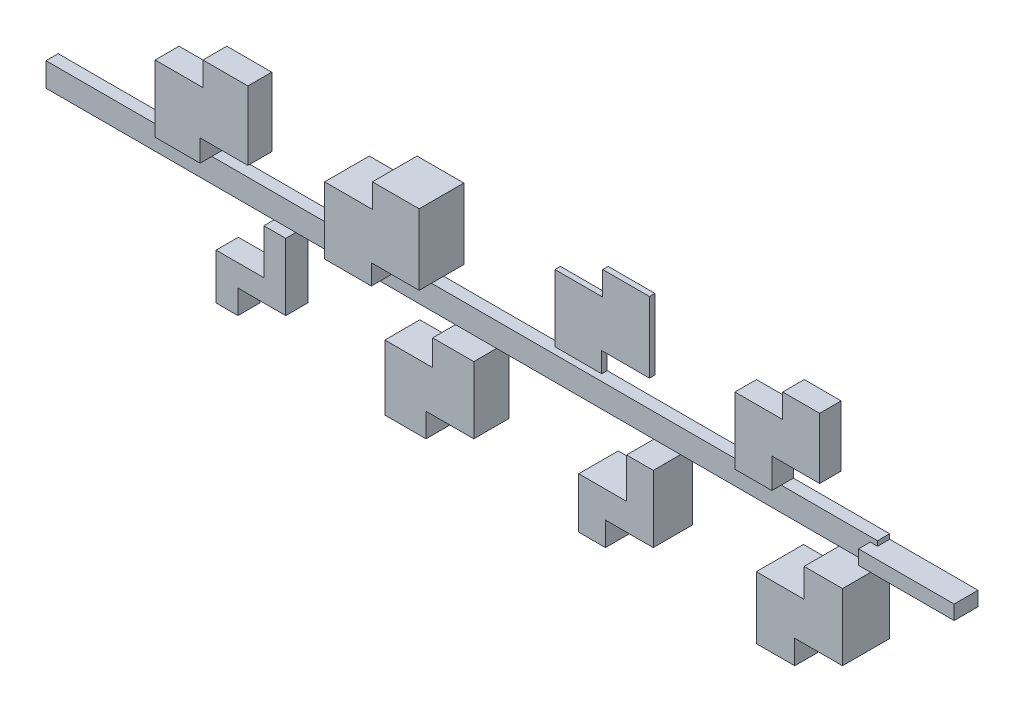
SolidWorks part; units mm, degrees
ref_plane "前视基准面" through (0, 0, 0) normal (0, 0, 1) x (1, 0, 0)
ref_plane "上视基准面" through (0, 0, 0) normal (0, 1, 0) x (1, 0, 0)
ref_plane "右视基准面" through (0, 0, 0) normal (1, 0, 0) x (0, 0, -1)
sketch "草图1" plane through (0, 0, 0) normal (0, 0, 1) x (1, 0, 0)
  line L1 (-9, 0.25) -> (9, 0.25)
  line L2 (-9, 0.25) -> (-9, -0.25)
  line L3 (-9, -0.25) -> (9, -0.25)
  line L4 (9, 0.25) -> (9, -0.25)
  line L5 (-9, 0.25) -> (9, -0.25) construction
  line L6 (-9, -0.25) -> (9, 0.25) construction
  point P0 (0, 0)
extrude "凸台-拉伸1" add sketch "草图1" along normal blind 0.2546
sketch "草图2" plane through (0, 0, 0) normal (0, 0, 1) x (1, 0, 0)
  line L0 (-9, 0) -> (-7, 0) construction
  line L3 (-9, 0.25) -> (-9, -0.25) construction
  line L4 (-7, -2.15) -> (-7, 2.15) construction
  line L5 (-7, 0) -> (-5, 0) construction
  line L6 (-5, -3) -> (-5, 3) construction
  line L7 (-3, -2.15) -> (-3, 2.15) construction
  line L8 (-1, -3) -> (-1, 3) construction
  line L9 (1, -2.15) -> (1, 2.15) construction
  line L10 (3, -3) -> (3, 3) construction
  line L11 (5, -2.15) -> (5, 2.15) construction
  line L12 (7, -3) -> (7, 3) construction
  line L13 (-7, -2.15) -> (-3, -2.15) construction
  line L14 (9, -2.15) -> (9, 2.15) construction
  line L15 (-7, -2.15) -> (9, -2.15) construction
  line L16 (-7, 2.15) -> (9, 2.15) construction
  point P8 (-7, 0)
  dimension "D1" = 4
  dimension "D2" = 4
  dimension "D4" = 16
  dimension "D3" = 2
sketch "草图3" plane through (0, 0, 0) normal (0, 0, 1) x (1, 0, 0)
  line L0 (9, 0) -> (10, 0) construction
  line L1 (9, -2.15) -> (9, 2.15) construction
  line L3 (9, 0.15) -> (11, 0.15)
  line L4 (9, 0.15) -> (9, -0.15)
  line L5 (9, -0.15) -> (11, -0.15)
  line L6 (11, 0.15) -> (11, -0.15)
  line L7 (9, 0.15) -> (11, -0.15) construction
  line L8 (9, -0.15) -> (11, 0.15) construction
extrude "凸台-拉伸2" [suppressed] add sketch "草图3" along normal blind 0.1 separate body
sketch "草图5" plane through (0, 0, 0) normal (0, 0, 1) x (1, 0, 0)
  line L0 (-5, 2.15) -> (-5.4705, 2.15) construction
  line L6 (-5, -3) -> (-5, 3) construction
  line L7 (-7, 2.15) -> (9, 2.15) construction
  line L8 (-5.4705, 2.15) -> (-5.4705, 1.65)
  line L9 (-5.4705, 1.65) -> (-6.4705, 1.65)
  line L10 (-6.4705, 1.65) -> (-6.4705, 0.25)
  line L11 (9, 0.25) -> (-9, 0.25) construction
  line L12 (-4.5295, 2.15) -> (-4.5295, 0.709)
  line L13 (-4.5295, 0.709) -> (-5.5295, 0.709)
  line L14 (-5.5295, 0.709) -> (-5.5295, 0.25)
  line L15 (-6.4705, 0.25) -> (-5.5295, 0.25)
  line L16 (-5.4705, 2.15) -> (-4.5295, 2.15)
  dimension "D3" = 1
  dimension "D2" = 0.941
extrude "凸台-拉伸3" add sketch "草图5" along normal blind 0.5 separate body
fillet "圆角1" [suppressed] radius 0.2
sketch "草图6" plane through (0, 0, 0) normal (0, 0, 1) x (1, 0, 0)
  line L0 (-1, 2.15) -> (-1.489, 2.15)
  line L1 (-0.511, 1.303) -> (-0.511, 1.303)
  line L2 (-1, -3) -> (-1, 3) construction
  line L3 (-7, 2.15) -> (9, 2.15) construction
  line L4 (-1.489, 2.15) -> (-1.489, 1.65)
  line L5 (-0.511, 1.303) -> (-0.511, 0.672)
  line L6 (-1.489, 1.65) -> (-2.489, 1.65)
  line L7 (-2.489, 1.65) -> (-2.489, 0.25)
  line L8 (9, 0.25) -> (-9, 0.25) construction
  line L9 (-0.511, 0.672) -> (-1.511, 0.6719)
  line L10 (-1.511, 0.6719) -> (-1.511, 0.25)
  line L11 (-2.489, 0.25) -> (-1.511, 0.25)
  line L12 (-1, 2.15) -> (-0.511, 2.15)
  line L13 (-0.511, 2.15) -> (-0.511, 1.303)
  dimension "D2" = 1
  dimension "D3" = 0.5
extrude "凸台-拉伸4" add sketch "草图6" along normal blind 0.9347 separate body
sketch "草图7" plane through (0, 0, 0) normal (0, 0, 1) x (1, 0, 0)
  line L0 (3, 2.15) -> (2.5103, 2.15)
  line L3 (3, -3) -> (3, 3) construction
  line L4 (-7, 2.15) -> (9, 2.15) construction
  line L5 (2.5103, 2.15) -> (2.5103, 1.65)
  line L6 (2.5103, 1.65) -> (1.5103, 1.65)
  line L7 (1.5103, 1.65) -> (1.5103, 0.25)
  line L8 (9, 0.25) -> (-9, 0.25) construction
  line L9 (3.4897, 1.3018) -> (3.4897, 1.3018)
  line L10 (3.4897, 1.3018) -> (3.4897, 0.6706)
  line L11 (3.4897, 0.6706) -> (2.4897, 0.6706)
  line L12 (2.4897, 0.6706) -> (2.4897, 0.25)
  line L13 (3.4897, 1.3018) -> (3.4897, 2.15)
  line L14 (3.4897, 2.15) -> (3, 2.15)
  line L15 (1.5103, 0.25) -> (2.4897, 0.25)
  dimension "D3" = 1
  dimension "D2" = 0.5
extrude "凸台-拉伸5" add sketch "草图7" along normal blind 0.1145 separate body
sketch "草图8" plane through (0, 0, 0) normal (0, 0, 1) x (1, 0, 0)
  line L0 (7, 2.15) -> (6.6137, 2.15)
  line L1 (7, -3) -> (7, 3) construction
  line L2 (-7, 2.15) -> (9, 2.15) construction
  line L3 (6.6137, 2.15) -> (6.6137, 1.65)
  line L4 (6.6137, 1.65) -> (5.6137, 1.65)
  line L5 (5.6137, 1.65) -> (5.6137, 0.25)
  line L6 (9, 0.25) -> (-9, 0.25) construction
  line L7 (7.3863, 1.4809) -> (7.3863, 1.4809)
  line L8 (7.3863, 1.4809) -> (7.3863, 0.8774)
  line L9 (7.3863, 0.8774) -> (6.3863, 0.8774)
  line L10 (6.3863, 0.8774) -> (6.3863, 0.25)
  line L11 (5.6137, 0.25) -> (6.3863, 0.25)
  line L13 (7.3863, 1.4809) -> (7.3863, 2.15)
  line L14 (7.3863, 2.15) -> (7, 2.15)
  dimension "D3" = 0.5
  dimension "D2" = 0.3863
  dimension "D4" = 1
  dimension "D1" = 0.7726
extrude "凸台-拉伸6" add sketch "草图8" along normal blind 0.4503 separate body
sketch "草图9" plane through (0, 0, 0) normal (0, 0, 1) x (1, 0, 0)
  line L0 (-5, -2.15) -> (-4.7709, -2.15)
  line L1 (-7, -2.15) -> (-3, -2.15) construction
  line L2 (-4.7709, -2.15) -> (-4.7709, -1.65)
  line L3 (-4.7709, -1.65) -> (-3.7709, -1.65)
  line L4 (-3.7709, -1.65) -> (-3.7709, -0.25)
  line L5 (-9, -0.25) -> (9, -0.25) construction
  line L6 (-5.2291, -2.15) -> (-5.2291, -1.1918)
  line L7 (-5.2291, -1.1918) -> (-4.2291, -1.1918)
  line L8 (-4.2291, -1.1918) -> (-4.2291, -0.25)
  line L9 (-4.2291, -0.25) -> (-3.7709, -0.25)
  line L13 (-5.2291, -2.15) -> (-5, -2.15)
  dimension "D3" = 1
  dimension "D2" = 0.5
  dimension "D1" = 0.2291
  dimension "D4" = 0.4582
extrude "凸台-拉伸7" add sketch "草图9" along normal blind 0.4667 separate body
sketch "草图11" plane through (0, 0, 0) normal (0, 0, 1) x (1, 0, 0)
  line L0 (-1, -2.15) -> (-0.5695, -2.15)
  line L1 (-1, -3) -> (-1, 3) construction
  line L2 (-7, -2.15) -> (9, -2.15) construction
  line L3 (-0.5695, -2.15) -> (-0.5695, -1.65)
  line L4 (-0.5695, -1.65) -> (0.4305, -1.65)
  line L5 (0.4305, -1.65) -> (0.4305, -0.25)
  line L6 (-9, -0.25) -> (9, -0.25) construction
  line L7 (-1.4305, -1.4044) -> (-1.4305, -1.4044)
  line L8 (-1.4305, -1.4044) -> (-1.4305, -0.7891)
  line L9 (-1.4305, -0.7891) -> (-0.4305, -0.7891)
  line L10 (-0.4305, -0.7891) -> (-0.4305, -0.25)
  line L11 (-0.4305, -0.25) -> (0.4305, -0.25)
  line L12 (-1.4305, -1.4044) -> (-1.4305, -2.15)
  line L13 (-1.4305, -2.15) -> (-1, -2.15)
  dimension "D3" = 0.5
  dimension "D4" = 1
  dimension "D2" = 0.4305
  dimension "D1" = 0.8609
extrude "凸台-拉伸8" add sketch "草图11" along normal blind 0.7323 separate body
sketch "草图12" plane through (0, 0, 0) normal (0, 0, 1) x (1, 0, 0)
  line L0 (3, -2.15) -> (3.2796, -2.15)
  line L1 (3, -3) -> (3, 3) construction
  line L2 (-7, -2.15) -> (9, -2.15) construction
  line L3 (3.2796, -2.15) -> (3.2796, -1.65)
  line L4 (3.2796, -1.65) -> (4.2796, -1.65)
  line L5 (4.2796, -1.65) -> (4.2796, -0.25)
  line L6 (-9, -0.25) -> (9, -0.25) construction
  line L7 (2.7204, -1.6657) -> (2.7204, -1.6657)
  line L8 (2.7204, -1.6657) -> (2.7204, -1.0907)
  line L9 (2.7204, -1.0907) -> (3.7204, -1.0907)
  line L10 (3.7204, -1.0907) -> (3.7204, -0.25)
  line L11 (3.7204, -0.25) -> (4.2796, -0.25)
  line L12 (2.7204, -1.6657) -> (2.7204, -2.15)
  line L13 (2.7204, -2.15) -> (3, -2.15)
  dimension "D3" = 1
  dimension "D2" = 0.2796
  dimension "D4" = 0.5
  dimension "D1" = 0.5593
extrude "凸台-拉伸9" add sketch "草图12" along normal blind 0.8258 separate body
sketch "草图13" plane through (0, 0, 0) normal (0, 0, 1) x (1, 0, 0)
  line L0 (7, -2.15) -> (7.4021, -2.15)
  line L1 (7, -3) -> (7, 3) construction
  line L2 (-7, -2.15) -> (9, -2.15) construction
  line L3 (7.4021, -2.15) -> (7.4021, -1.65)
  line L4 (7.4021, -1.65) -> (8.4021, -1.65)
  line L5 (8.4021, -1.65) -> (8.4021, -0.25)
  line L6 (-9, -0.25) -> (9, -0.25) construction
  line L7 (6.5979, -1.4536) -> (6.5979, -1.4536)
  line L8 (6.5979, -1.4536) -> (6.5979, -0.8459)
  line L9 (6.5979, -0.8459) -> (7.5979, -0.8459)
  line L10 (7.5979, -0.8459) -> (7.5979, -0.25)
  line L11 (6.5979, -1.4536) -> (6.5979, -2.15)
  line L12 (6.5979, -2.15) -> (7, -2.15)
  line L13 (7.5979, -0.25) -> (8.4021, -0.25)
  dimension "D3" = 0.5
  dimension "D4" = 1
  dimension "D2" = 0.4021
  dimension "D1" = 0.8041
extrude "凸台-拉伸10" add sketch "草图13" along normal blind 0.9874 separate body
sketch "草图14" plane through (9, 0, 0) normal (1, 0, 0) x (0, 0, -1)
  line L4 (0, -0.25) -> (0, 0.25)
  line L5 (0, 0.25) -> (-0.2546, 0.25)
  line L6 (-0.2546, 0.25) -> (-0.2546, -0.25)
  line L7 (-0.2546, -0.25) -> (0, -0.25)
  line L8 (0, -0.25) -> (0, 0.25)
  line L9 (0, 0.25) -> (-0.2546, 0.25)
  line L10 (-0.2546, 0.25) -> (-0.2546, -0.25)
  line L11 (-0.2546, -0.25) -> (0, -0.25)
  dimension "D1" = 0
extrude "切除-拉伸1" cut sketch "草图14" against normal up to surface (0.5979 mm away) up to face at (8.4021, -0.95, 0.4937)
sketch "草图15" plane through (0, 0, 0) normal (0, 0, 1) x (1, 0, 0)
  line L0 (8.4021, 0) -> (9.25, 0) construction
  line L1 (8.4021, 0.25) -> (8.4021, -0.25) construction
  line L3 (8.25, 0.15) -> (10.25, 0.15)
  line L4 (8.25, 0.15) -> (8.25, -0.15)
  line L5 (8.25, -0.15) -> (10.25, -0.15)
  line L6 (10.25, 0.15) -> (10.25, -0.15)
  line L7 (8.25, 0.15) -> (10.25, -0.15) construction
  line L8 (8.25, -0.15) -> (10.25, 0.15) construction
extrude "凸台-拉伸11" add sketch "草图15" along normal blind 0.5 separate body
equation "\"D1@草图5\"=\"w1\""
equation "\"D2@草图5\"=\"d1\""
equation "\"D3@草图5\"=\"L\""
equation "\"L\"= 1mm"
equation "\"d1\"=0.94101mm"
equation "\"w1\"= \"d1\" / 2"
equation "\"h1\"=0.45342mm"
equation "\"h2\"=0.46671mm"
equation "\"d2\"=0.45815mm"
equation "\"w2\"= \"d2\" / 2"
equation "\"h3\"=0.93474mm"
equation "\"d3\"=0.9780500000000001mm"
equation "\"w3\"= \"d3\" / 2"
equation "\"h4\"=0.7322700000000001mm"
equation "\"d4\"=0.86094mm"
equation "\"w4\"= \"d4\" / 2"
equation "\"h5\"=0.11451mm"
equation "\"d5\"=0.97942mm"
equation "\"w5\"= \"d5\" / 2"
equation "\"h6\"=0.82582mm"
equation "\"d6\"=0.55925mm"
equation "\"w6\"= \"d6\" / 2"
equation "\"h7\"=0.45035mm"
equation "\"d7\"=0.77258mm"
equation "\"w7\"= \"d7\" / 2"
equation "\"h8\"=0.9874500000000002mm"
equation "\"d8\"=0.80412mm"
equation "\"w8\"= \"d8\" / 2"
equation "\"D1@凸台-拉伸4\"=\"h3\""
equation "\"D1@草图6\"=\"w3\""
equation "\"D4@草图6\"=\"d3\""
equation "\"D1@草图7\"=\"w5\""
equation "\"D1@凸台-拉伸5\"=\"h5\""
equation "\"D2@草图8\"=\"w7\""
equation "\"D1@凸台-拉伸6\"=\"h7\""
equation "\"D1@草图8\"=\"d7\""
equation "\"D4@草图7\"=\"d5\""
equation "\"D1@草图9\"=\"w2\""
equation "\"D4@草图9\"=\"d2\""
equation "\"D1@凸台-拉伸7\"=\"h2\""
equation "\"D1@草图11\"=\"d4\""
equation "\"D2@草图11\"=\"w4\""
equation "\"D1@凸台-拉伸8\"=\"h4\""
equation "\"D2@草图12\"=\"w6\""
equation "\"D1@草图12\"=\"d6\""
equation "\"D1@凸台-拉伸9\"=\"h6\""
equation "\"D2@草图13\"=\"w8\""
equation "\"D1@草图13\"=\"d8\""
equation "\"D1@凸台-拉伸10\"=\"h8\""
equation "\"chhei\"=0.25457mm"
equation "\"D1@凸台-拉伸1\" = \"chhei\""
